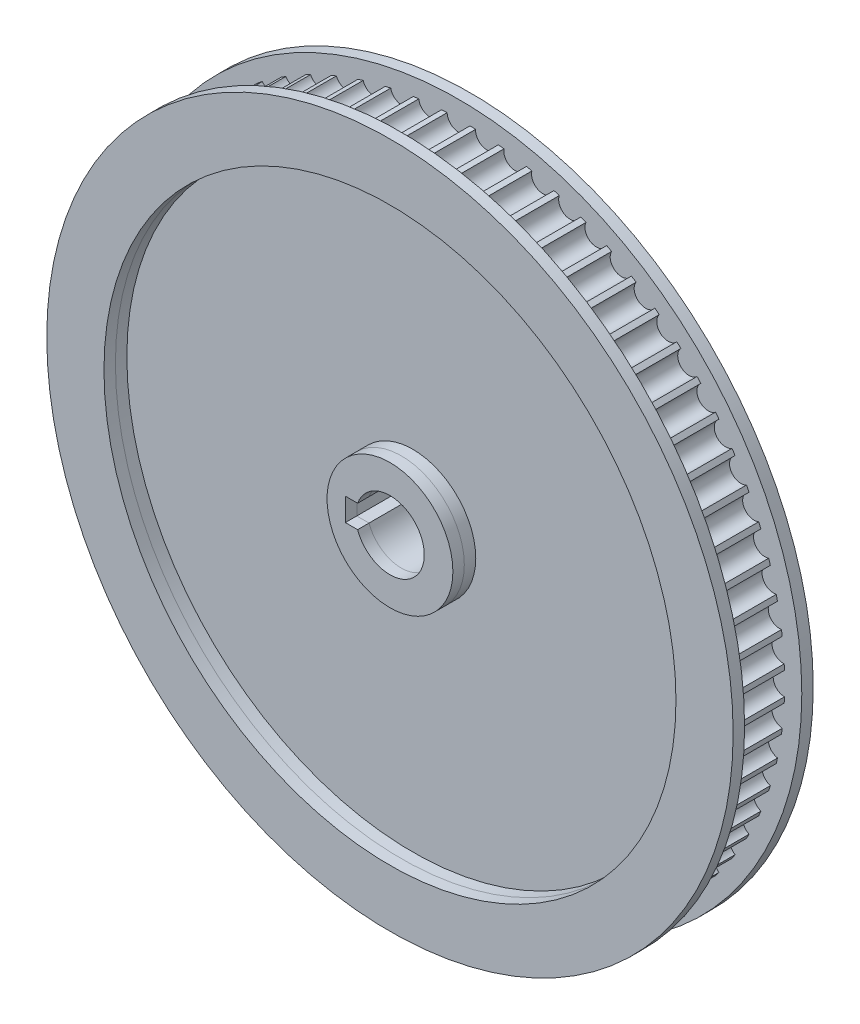
SolidWorks part; units mm, degrees
ref_plane "前视基准面" through (0, 0, 0) normal (0, 0, 1) x (1, 0, 0)
ref_plane "上视基准面" through (0, 0, 0) normal (0, 1, 0) x (1, 0, 0)
ref_plane "右视基准面" through (0, 0, 0) normal (1, 0, 0) x (0, 0, -1)
sketch "Sketch1" plane through (0, 0, 0) normal (0, 0, 1) x (1, 0, 0)
  circle A0 centre (0, 0) radius 57
  dimension "D1" = 114
extrude "Boss-Extrude1" add sketch "Sketch1" along normal blind 10
sketch "Sketch5" plane through (0, 0, 10) normal (0, 0, 1) x (1, 0, 0)
  circle A0 centre (0, 0) radius 6
  dimension "D1" = 12
extrude "Cut-Extrude4" cut sketch "Sketch5" against normal up to next
sketch "KeySketch" plane through (-8.6294, -14.177, 10) normal (0, 0, 1) x (1, 0, 0)
  line L0 (14.6294, 14.177) -> (0.8294, 14.177) construction
  line L1 (8.6294, 8.177) -> (8.6294, 20.177) construction
  line L2 (2.9725, 12.177) -> (0.8294, 12.177)
  line L3 (17.2266, 14.177) -> (-22.7774, 14.177) construction
  line L4 (0.8294, 16.177) -> (2.9725, 16.177)
  line L5 (0.8294, 16.177) -> (0.8294, 12.177)
  arc A0 (2.9725, 12.177) -> (2.9725, 16.177) centre (8.6294, 14.177) ccw
  circle A1 centre (8.6294, 14.177) radius 6 construction
  point P10 (0.8294, 14.177)
  dimension "D1" = 180
  dimension "Diameter" = 12
  dimension "Width" = 4
  dimension "Depth" = 1.8
extrude "Keyway" cut sketch "KeySketch" against normal through all
other "bore with square keyway bs 4500p1<1>"
sketch "Sketch8" plane through (0, 0, 0) normal (0, 0, -1) x (-1, 0, 0)
  circle A0 centre (0, 0) radius 11
  circle A1 centre (0, 0) radius 50
  dimension "D1" = 100
extrude "Cut-Extrude6" cut sketch "Sketch8" against normal blind 2
sketch "Sketch9" plane through (0, 0, 10) normal (0, 0, 1) x (1, 0, 0)
  circle A0 centre (0, 0) radius 11
  circle A1 centre (0, 0) radius 50
  dimension "D1" = 100
extrude "Cut-Extrude7" cut sketch "Sketch9" against normal blind 2
sketch "Sketch11" plane through (0, 0, 0) normal (0, 0, -1) x (-1, 0, 0)
  line L0 (5.6569, -2) -> (7.8, -2) construction
  line L1 (7.8, 2) -> (7.8, -2) construction
  line L2 (7.8, 2) -> (5.6569, 2) construction
  line L3 (5.6569, -2) -> (7.8, -2)
  line L4 (7.8, 2) -> (7.8, -2)
  line L5 (7.8, 2) -> (5.6569, 2)
  circle A0 centre (0, 0) radius 50
  circle A1 centre (0, 0) radius 60
  circle A2 centre (0, 0) radius 11 construction
  arc A3 (5.6569, 2) -> (5.6569, -2) centre (0, 0) ccw construction
  circle A4 centre (0, 0) radius 11
  arc A5 (5.6569, 2) -> (5.6569, -2) centre (0, 0) ccw
  circle M3 centre (0, 0) radius 50
  circle M4 centre (0, 0) radius 57
  dimension "D1" = 120
extrude "Boss-Extrude2" add sketch "Sketch11" along normal blind 2 contours A1 M4 | M4 M3 | A4 A5 L5 L4 L3
sketch "Sketch12" plane through (0, 0, 10) normal (0, 0, 1) x (1, 0, 0)
  line L0 (-5.6569, -2) -> (-7.8, -2) construction
  line L1 (-7.8, 2) -> (-7.8, -2) construction
  line L2 (-7.8, 2) -> (-5.6569, 2) construction
  line L3 (-5.6569, -2) -> (-7.8, -2)
  line L4 (-7.8, 2) -> (-7.8, -2)
  line L5 (-7.8, 2) -> (-5.6569, 2)
  circle A1 centre (0, 0) radius 60
  circle A2 centre (0, 0) radius 50
  arc A3 (-5.6569, -2) -> (-5.6569, 2) centre (0, 0) ccw construction
  circle A4 centre (0, 0) radius 11 construction
  arc A5 (-5.6569, -2) -> (-5.6569, 2) centre (0, 0) ccw
  circle A6 centre (0, 0) radius 11
  circle M3 centre (0, 0) radius 50
  circle M4 centre (0, 0) radius 57
extrude "Boss-Extrude3" add sketch "Sketch12" along normal blind 2 separate body contours A6 A5 L3 L4 L5 | M4 M3 | A1 M4
ref_plane "Plane1" through (0, 0, 5) normal (0, 0, 1) x (1, 0, 0)
sketch "Sketch10" plane through (0, 0, 5) normal (0, 0, 1) x (1, 0, 0)
  circle A0 centre (0, 57) radius 2
  circle A1 centre (0, 0) radius 57 construction
  circle A2 centre (4.9679, 56.7831) radius 2
  circle A3 centre (9.8979, 56.134) radius 2
  circle A4 centre (14.7527, 55.0578) radius 2
  circle A5 centre (19.4951, 53.5625) radius 2
  circle A6 centre (24.0892, 51.6595) radius 2
  circle A7 centre (28.5, 49.3634) radius 2
  circle A8 centre (32.6939, 46.6917) radius 2
  circle A9 centre (36.6389, 43.6645) radius 2
  circle A10 centre (40.3051, 40.3051) radius 2
  circle A11 centre (43.6645, 36.6389) radius 2
  circle A12 centre (46.6917, 32.6939) radius 2
  circle A13 centre (49.3634, 28.5) radius 2
  circle A14 centre (51.6595, 24.0892) radius 2
  circle A15 centre (53.5625, 19.4951) radius 2
  circle A16 centre (55.0578, 14.7527) radius 2
  circle A17 centre (56.134, 9.8979) radius 2
  circle A18 centre (56.7831, 4.9679) radius 2
  circle A19 centre (57, 0) radius 2
  circle A20 centre (56.7831, -4.9679) radius 2
  circle A21 centre (56.134, -9.8979) radius 2
  circle A22 centre (55.0578, -14.7527) radius 2
  circle A23 centre (53.5625, -19.4951) radius 2
  circle A24 centre (51.6595, -24.0892) radius 2
  circle A25 centre (49.3634, -28.5) radius 2
  circle A26 centre (46.6917, -32.6939) radius 2
  circle A27 centre (43.6645, -36.6389) radius 2
  circle A28 centre (40.3051, -40.3051) radius 2
  circle A29 centre (36.6389, -43.6645) radius 2
  circle A30 centre (32.6939, -46.6917) radius 2
  circle A31 centre (28.5, -49.3634) radius 2
  circle A32 centre (24.0892, -51.6595) radius 2
  circle A33 centre (19.4951, -53.5625) radius 2
  circle A34 centre (14.7527, -55.0578) radius 2
  circle A35 centre (9.8979, -56.134) radius 2
  circle A36 centre (4.9679, -56.7831) radius 2
  circle A37 centre (0, -57) radius 2
  circle A38 centre (-4.9679, -56.7831) radius 2
  circle A39 centre (-9.8979, -56.134) radius 2
  circle A40 centre (-14.7527, -55.0578) radius 2
  circle A41 centre (-19.4951, -53.5625) radius 2
  circle A42 centre (-24.0892, -51.6595) radius 2
  circle A43 centre (-28.5, -49.3634) radius 2
  circle A44 centre (-32.6939, -46.6917) radius 2
  circle A45 centre (-36.6389, -43.6645) radius 2
  circle A46 centre (-40.3051, -40.3051) radius 2
  circle A47 centre (-43.6645, -36.6389) radius 2
  circle A48 centre (-46.6917, -32.6939) radius 2
  circle A49 centre (-49.3634, -28.5) radius 2
  circle A50 centre (-51.6595, -24.0892) radius 2
  circle A51 centre (-53.5625, -19.4951) radius 2
  circle A52 centre (-55.0578, -14.7527) radius 2
  circle A53 centre (-56.134, -9.8979) radius 2
  circle A54 centre (-56.7831, -4.9679) radius 2
  circle A55 centre (-57, 0) radius 2
  circle A56 centre (-56.7831, 4.9679) radius 2
  circle A57 centre (-56.134, 9.8979) radius 2
  circle A58 centre (-55.0578, 14.7527) radius 2
  circle A59 centre (-53.5625, 19.4951) radius 2
  circle A60 centre (-51.6595, 24.0892) radius 2
  circle A61 centre (-49.3634, 28.5) radius 2
  circle A62 centre (-46.6917, 32.6939) radius 2
  circle A63 centre (-43.6645, 36.6389) radius 2
  circle A64 centre (-40.3051, 40.3051) radius 2
  circle A65 centre (-36.6389, 43.6645) radius 2
  circle A66 centre (-32.6939, 46.6917) radius 2
  circle A67 centre (-28.5, 49.3634) radius 2
  circle A68 centre (-24.0892, 51.6595) radius 2
  circle A69 centre (-19.4951, 53.5625) radius 2
  circle A70 centre (-14.7527, 55.0578) radius 2
  circle A71 centre (-9.8979, 56.134) radius 2
  circle A72 centre (-4.9679, 56.7831) radius 2
  dimension "D1" = 72
extrude "Cut-Extrude8" cut sketch "Sketch10" against normal mid plane 10
